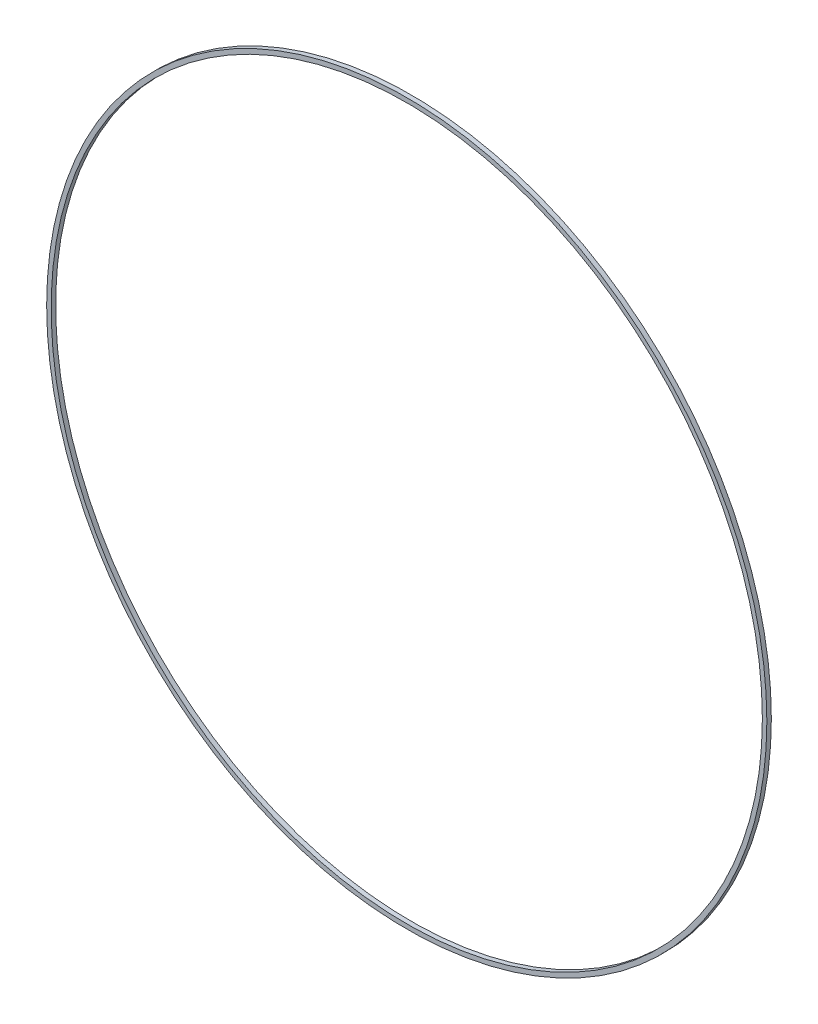
SolidWorks part; units mm, degrees
ref_plane "Front Plane" through (0, 0, 0) normal (0, 0, 1) x (1, 0, 0)
ref_plane "Top Plane" through (0, 0, 0) normal (0, 1, 0) x (1, 0, 0)
ref_plane "Right Plane" through (0, 0, 0) normal (1, 0, 0) x (0, 0, -1)
sketch "Sketch1" plane through (0, 0, 0) normal (0, 0, 1) x (1, 0, 0)
  circle A0 centre (-24.8526, 9.2304) radius 100.4018
  circle A1 centre (-24.8526, 9.2304) radius 101.6718
  dimension "D1" = 1.27
extrude "Boss-Extrude1" add sketch "Sketch1" along normal blind 1.27
